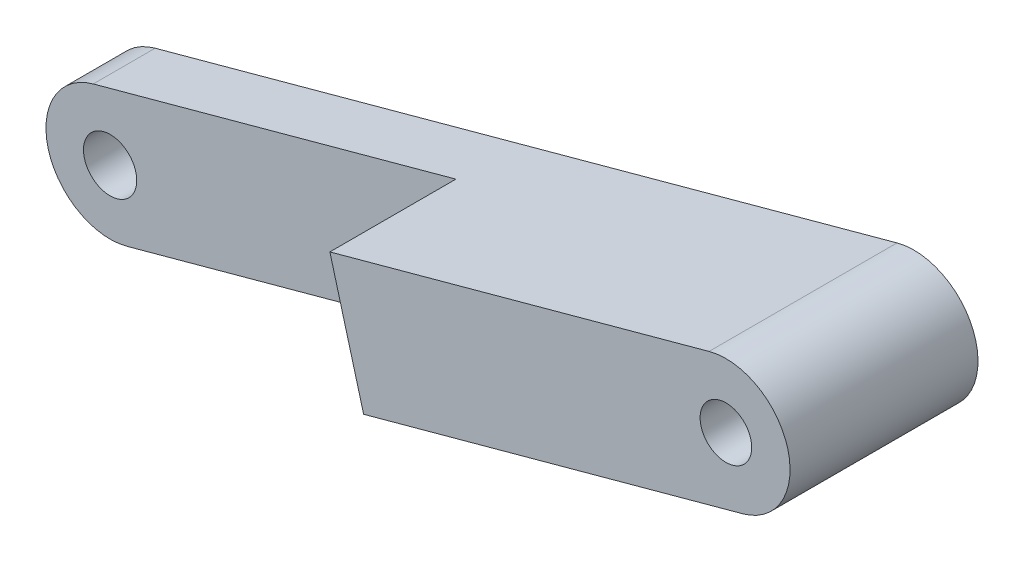
SolidWorks part; units mm, degrees
ref_plane "Plan de face" through (0, 0, 0) normal (0, 0, 1) x (1, 0, 0)
ref_plane "Plan de dessus" through (0, 0, 0) normal (0, 1, 0) x (1, 0, 0)
ref_plane "Plan de droite" through (0, 0, 0) normal (1, 0, 0) x (0, 0, -1)
sketch "Esquisse1" plane through (0, 0, 0) normal (0, 0, 1) x (1, 0, 0)
  line L0 (-26.5993, 1.1673) -> (16.8153, 13.007) construction
  line L5 (-27.5868, 4.7886) -> (15.8277, 16.6283)
  line L6 (-25.6117, -2.454) -> (17.8028, 9.3857)
  arc A8 (-27.5868, 4.7886) -> (-25.6117, -2.454) centre (-26.5993, 1.1673) ccw
  arc A9 (17.8028, 9.3857) -> (15.8277, 16.6283) centre (16.8153, 13.007) ccw
  circle A10 centre (-26.5993, 1.1673) radius 1.5587
  circle A11 centre (16.8153, 13.007) radius 1.5107
  point P2 (-23.4335, -5.5759)
  point P3 (-18.7723, -15.396)
  point P4 (-4.892, 7.0872)
  dimension "D1" = 45
extrude "Boss.-Extru.1" add sketch "Esquisse1" along normal blind 11
sketch "Esquisse2" plane through (-3.1252, 11.4596, 0) normal (-0.2631, 0.9648, 0) x (0.9648, 0.2631, 0)
  line L0 (-29.1085, -11) -> (-25.355, -11) construction
  line L1 (-33.355, -11) -> (-3.355, -11)
  line L2 (-33.355, -11) -> (-33.355, -3.6232)
  line L3 (-33.355, -3.6232) -> (-3.355, -3.6232)
  line L4 (-3.355, -11) -> (-3.355, -3.6232)
  line L5 (-25.355, -11) -> (-25.355, 0) construction
  dimension "D1" = 30
  dimension "D2" = 8
extrude "Enlèv. mat.-Extru.1" cut sketch "Esquisse2" against normal blind 10
